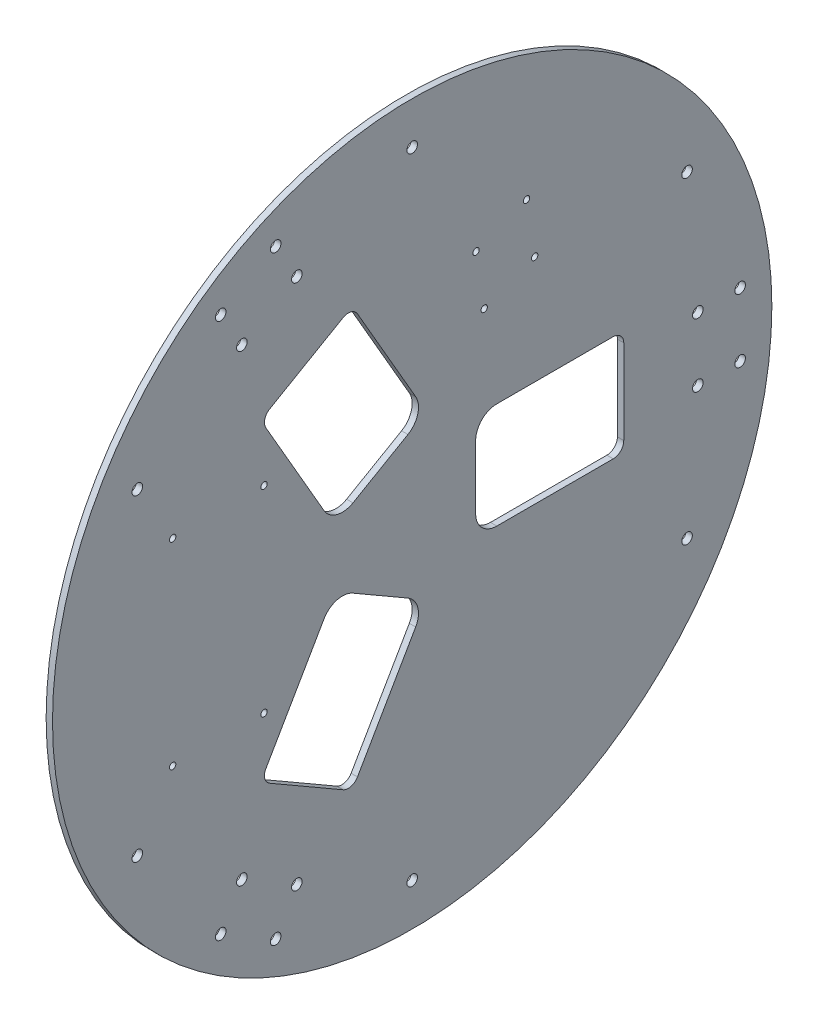
SolidWorks part; units mm, degrees
ref_plane "前视基准面" through (0, 0, 0) normal (0, 0, 1) x (1, 0, 0)
ref_plane "上视基准面" through (0, 0, 0) normal (0, 1, 0) x (1, 0, 0)
ref_plane "右视基准面" through (0, 0, 0) normal (1, 0, 0) x (0, 0, -1)
sketch "草图1" plane through (0, 0, 0) normal (1, 0, 0) x (0, 0, -1)
  line L0 (0, 0) -> (269.4466, 0) construction
  line L1 (0, 0) -> (-109.9408, 190.4231) construction
  line L2 (0, 0) -> (-109.9408, -190.4231) construction
  line L3 (100, 0) -> (100, 20)
  line L4 (100, 0) -> (100, -20)
  line L5 (-50, 86.6025) -> (-67.3205, 76.6025)
  line L6 (-50, 86.6025) -> (-32.6795, 96.6025)
  line L7 (0, 0) -> (-108, 0) construction
  line L8 (-50, -86.6025) -> (-32.6795, -96.6025)
  line L9 (-50, -86.6025) -> (-67.3205, -76.6025)
  line L10 (0, 135) -> (116.9134, 67.5) construction
  line L11 (40, 25) -> (95, 25)
  line L12 (30, -15) -> (30, 15)
  line L13 (40, -25) -> (95, -25)
  line L14 (-41.6506, 22.141) -> (-69.1506, 69.7724)
  line L15 (-27.9904, 18.4808) -> (-2.0096, 33.4808)
  line L16 (1.6506, 47.141) -> (-25.8494, 94.7724)
  line L17 (0, 0) -> (45.6985, -79.1521) construction
  line L18 (19.5096, -63.7917) -> (45.4904, -48.7917) construction
  line L19 (1.6506, -47.141) -> (-25.8494, -94.7724)
  line L20 (-2.0096, -33.4808) -> (-27.9904, -18.4808)
  line L21 (-41.6506, -22.141) -> (-69.1506, -69.7724)
  line L24 (36.6891, 133.5474) -> (97.3109, 98.5474) construction
  line L25 (97.3109, 98.5474) -> (60.3109, 34.4615) construction
  line L26 (60.3109, 34.4615) -> (-0.3109, 69.4615) construction
  line L27 (-0.3109, 69.4615) -> (36.6891, 133.5474) construction
  line L28 (58.4567, 101.25) -> (0, 0) construction
  circle A0 centre (0, 0) radius 170
  circle A1 centre (155, 15) radius 2.5
  circle A2 centre (135, 15) radius 2.5
  circle A3 centre (135, -15) radius 2.5
  circle A4 centre (155, -15) radius 2.5
  circle A5 centre (-90.4904, 126.7339) radius 2.5
  circle A6 centre (-80.4904, 109.4134) radius 2.5
  circle A7 centre (-54.5096, 124.4134) radius 2.5
  circle A8 centre (-64.5096, 141.7339) radius 2.5
  circle A9 centre (-64.5096, -141.7339) radius 2.5
  circle A10 centre (-54.5096, -124.4134) radius 2.5
  circle A11 centre (-80.4904, -109.4134) radius 2.5
  circle A12 centre (-90.4904, -126.7339) radius 2.5
  arc A13 (100, 20) -> (95, 25) centre (95, 20) ccw
  arc A14 (30, 15) -> (40, 25) centre (40, 15) cw
  arc A15 (100, -20) -> (95, -25) centre (95, -20) cw
  arc A16 (30, -15) -> (40, -25) centre (40, -15) ccw
  arc A17 (-27.9904, 18.4808) -> (-41.6506, 22.141) centre (-32.9904, 27.141) cw
  arc A18 (-67.3205, 76.6025) -> (-69.1506, 69.7724) centre (-64.8205, 72.2724) ccw
  arc A19 (-2.0096, 33.4808) -> (1.6506, 47.141) centre (-7.0096, 42.141) ccw
  arc A20 (-32.6795, 96.6025) -> (-25.8494, 94.7724) centre (-30.1795, 92.2724) cw
  arc A21 (-2.0096, -33.4808) -> (1.6506, -47.141) centre (-7.0096, -42.141) cw
  arc A22 (-32.6795, -96.6025) -> (-25.8494, -94.7724) centre (-30.1795, -92.2724) ccw
  arc A23 (-27.9904, -18.4808) -> (-41.6506, -22.141) centre (-32.9904, -27.141) ccw
  arc A24 (-67.3205, -76.6025) -> (-69.1506, -69.7724) centre (-64.8205, -72.2724) cw
  circle A25 centre (-70, 46.6) radius 1.5
  circle A26 centre (-113.2, 46.6) radius 1.5
  circle A27 centre (-113.2, -46.6) radius 1.5
  circle A28 centre (-70, -46.6) radius 1.5
  circle A29 centre (0, -150) radius 2.5
  circle A30 centre (-129.9038, -75) radius 2.5
  circle A31 centre (-129.9038, 75) radius 2.5
  circle A32 centre (0, 150) radius 2.5
  circle A33 centre (129.9038, 75) radius 2.5
  circle A34 centre (129.9038, -75) radius 2.5
  circle A35 centre (54.0359, 101.5929) radius 1.5
  circle A36 centre (34.0359, 66.9519) radius 1.5
  circle A37 centre (57.8923, 76.2724) radius 1.5
  circle A38 centre (30.1795, 92.2724) radius 1.5
  dimension "D1" = 340
  dimension "D2" = 5
  dimension "D7" = 3
  dimension "D8" = 3
  dimension "D10" = 43.2
  dimension "D14" = 5
  dimension "D15" = 70
  dimension "D18" = 10
  dimension "D19" = 5
  dimension "D20" = 30
  dimension "D21" = 70
  dimension "D22" = 74
  dimension "D24" = 19
  dimension "D28" = 3
  dimension "D29" = 3
  dimension "D30" = 3
  dimension "D31" = 3
  dimension "D41" = 30
  dimension "D47" = 30
  dimension "D52" = 5
  dimension "D54" = 6
  dimension "D5" = 93.2
  dimension "D6" = 135
  dimension "D9" = 70
  dimension "D11" = 155
  dimension "D12" = 15
  dimension "D13" = 20
  dimension "D16" = 50
  dimension "D17" = 30
  dimension "D23" = 35
  dimension "D25" = 39
  dimension "D26" = 39
  dimension "D27" = 59
  dimension "D32" = 23
  dimension "D33" = 55
  dimension "D34" = 39
  dimension "D35" = 39
  dimension "D36" = 60
  dimension "D37" = 30
  dimension "D38" = 30
  dimension "D39" = 20
  dimension "D40" = 30
  dimension "D42" = 20
  dimension "D44" = 30
  dimension "D45" = 60
  dimension "D46" = 67.5
  dimension "D48" = 65
  dimension "D43" = 20
  dimension "D49" = 30
  dimension "D50" = 20
  dimension "D51" = 20
  dimension "D53" = 150
  dimension "D55" = 150
  dimension "D56" = 150
extrude "凸台-拉伸1" add sketch "草图1" along normal blind 3
